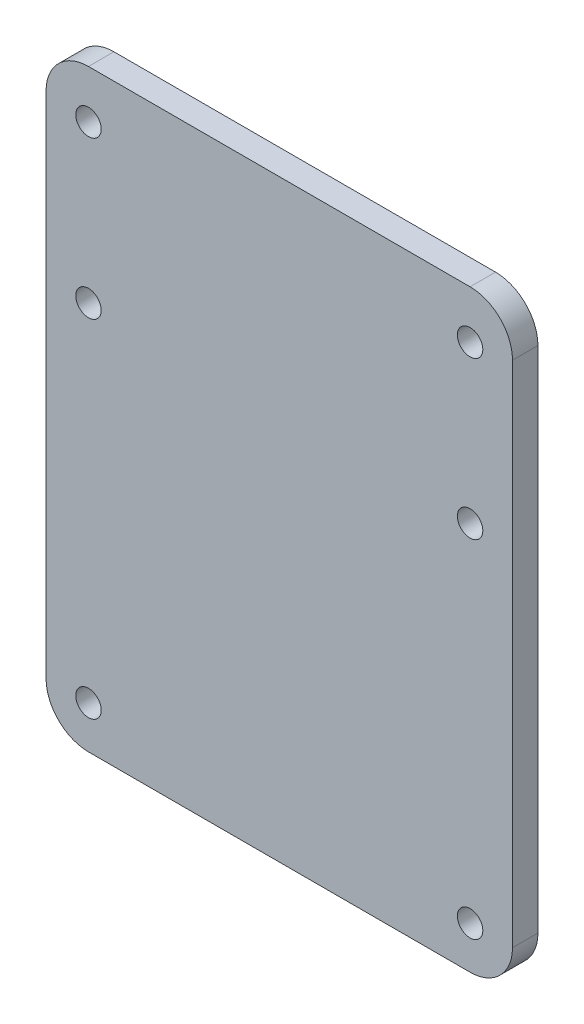
SolidWorks part; units mm, degrees
ref_plane "Front Plane" through (0, 0, 0) normal (0, 0, 1) x (1, 0, 0)
ref_plane "Top Plane" through (0, 0, 0) normal (0, 1, 0) x (1, 0, 0)
ref_plane "Right Plane" through (0, 0, 0) normal (1, 0, 0) x (0, 0, -1)
sketch "Sketch1" plane through (0, 0, 0) normal (0, 0, 1) x (1, 0, 0)
  line L1 (-25.7372, 42.2489) -> (29.2628, 42.2489)
  line L2 (-25.7372, 42.2489) -> (-25.7372, -27.7511)
  line L3 (-25.7372, -27.7511) -> (29.2628, -27.7511)
  line L4 (29.2628, 42.2489) -> (29.2628, -27.7511)
  dimension "D1" = 55
  dimension "D2" = 70
extrude "Boss-Extrude1" add sketch "Sketch1" along normal blind 3
sketch "Sketch2" plane through (0, 0, 3) normal (0, 0, 1) x (1, 0, 0)
  line L0 (-25.7372, 42.2489) -> (-25.7372, -27.7511) construction
  line L1 (-25.7372, -27.7511) -> (29.2628, -27.7511) construction
  circle A0 centre (-20.7372, 36.588) radius 1.5
  circle A1 centre (24.2628, 36.588) radius 1.5
  circle A2 centre (-20.7372, 18.088) radius 1.5
  circle A3 centre (24.2628, 18.088) radius 1.5
  circle A4 centre (-20.7372, -22.7511) radius 1.5
  circle A5 centre (24.2628, -22.7511) radius 1.5
  dimension "D3" = 3
  dimension "D4" = 3
  dimension "D6" = 3
  dimension "D7" = 3
  dimension "D8" = 3
  dimension "D9" = 3
  dimension "D1" = 45
  dimension "D2" = 5
  dimension "D5" = 18.5
  dimension "D10" = 5
extrude "Cut-Extrude1" cut sketch "Sketch2" against normal blind 3
fillet "Fillet1" radius 5 4 edges at (29.2628, -27.7511, 1.5) (-25.7372, -27.7511, 1.5) (-25.7372, 42.2489, 1.5) (29.2628, 42.2489, 1.5)
